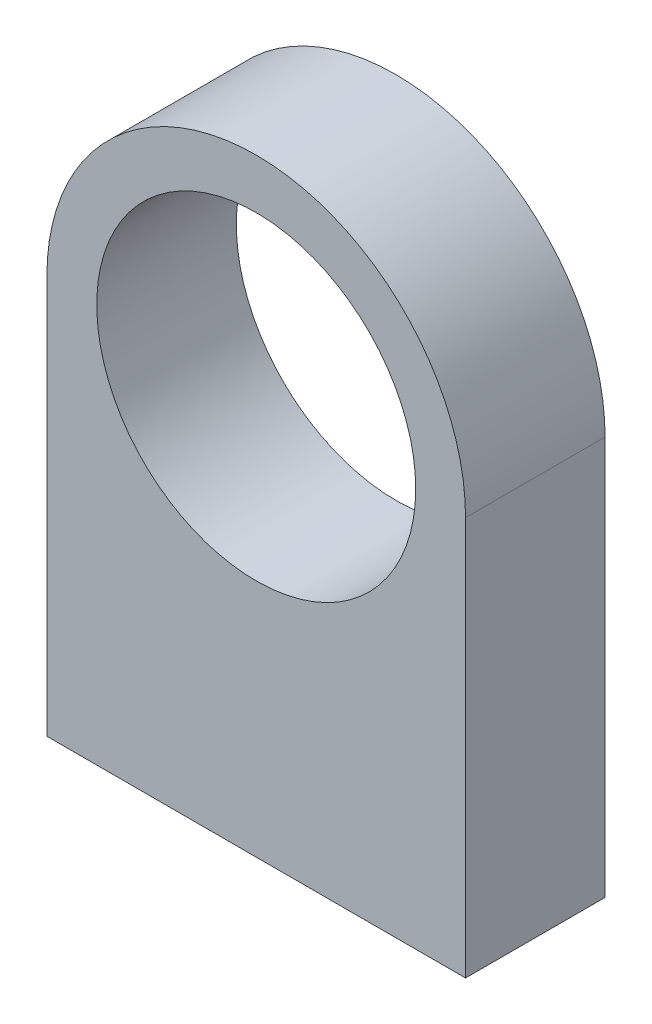
SolidWorks part; units mm, degrees
ref_plane "Alzado" through (0, 0, 0) normal (0, 0, 1) x (1, 0, 0)
ref_plane "Planta" through (0, 0, 0) normal (0, 1, 0) x (1, 0, 0)
ref_plane "Vista lateral" through (0, 0, 0) normal (1, 0, 0) x (0, 0, -1)
sketch "Croquis1" plane through (0, 0, 0) normal (0, 0, 1) x (1, 0, 0)
  line L1 (10.5, -10) -> (-10.5, -10)
  line L2 (10.5, -10) -> (10.5, 10)
  line L4 (-10.5, -10) -> (-10.5, 10)
  line L5 (10.5, -10) -> (-10.5, 10) construction
  line L6 (10.5, 10) -> (-10.5, -10) construction
  arc A0 (10.5, 10) -> (-10.5, 10) centre (0, 10) ccw
  point P0 (0, 0)
  dimension "D1" = 21
  dimension "D2" = 20
extrude "Saliente-Extruir1" add sketch "Croquis1" along normal mid plane 7
sketch "Croquis2" plane through (0, 0, 3.5) normal (0, 0, 1) x (1, 0, 0)
  circle A0 centre (0, 10) radius 8
  dimension "D1" = 16
extrude "Cortar-Extruir1" cut sketch "Croquis2" against normal through all
